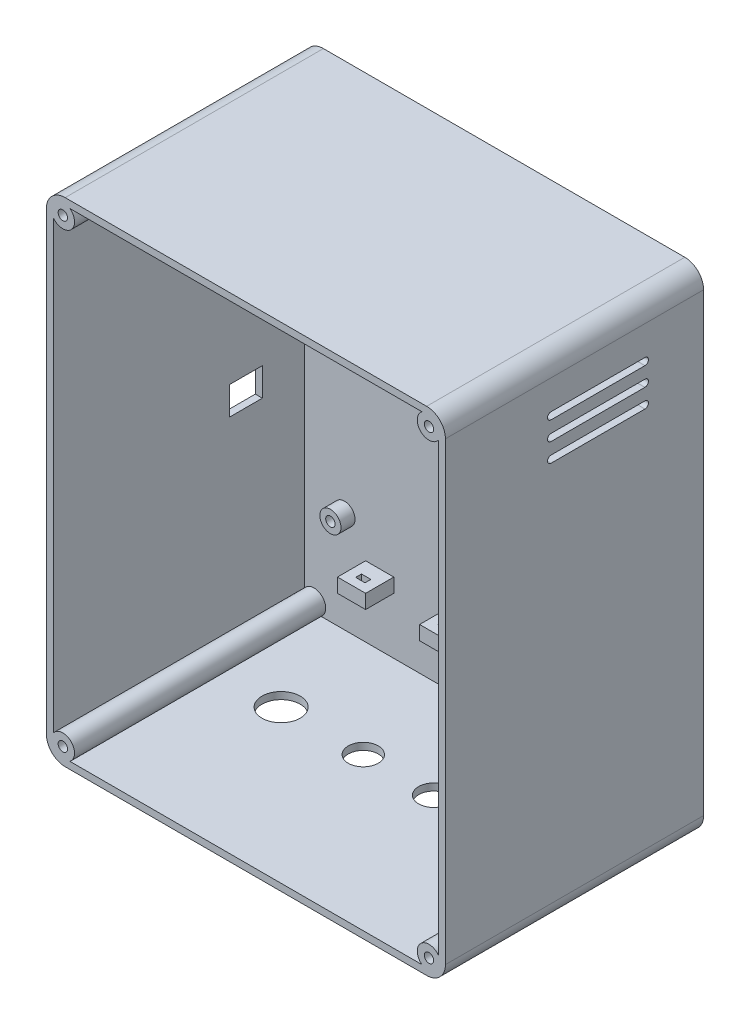
SolidWorks part; units mm, degrees
ref_plane "Front Plane" through (0, 0, 0) normal (0, 0, 1) x (1, 0, 0)
ref_plane "Top Plane" through (0, 0, 0) normal (0, 1, 0) x (1, 0, 0)
ref_plane "Right Plane" through (0, 0, 0) normal (1, 0, 0) x (0, 0, -1)
sketch "Sketch1" plane through (0, 0, 0) normal (0, 0, 1) x (1, 0, 0)
  line L0 (-77, 0) -> (77, 0)
  line L1 (85, 8) -> (85, 202)
  line L2 (77, 210) -> (-77, 210)
  line L3 (-85, 202) -> (-85, 8)
  arc A0 (-85, 8) -> (-77, 0) centre (-77, 8) ccw
  arc A1 (77, 0) -> (85, 8) centre (77, 8) ccw
  arc A2 (85, 202) -> (77, 210) centre (77, 202) ccw
  arc A3 (-77, 210) -> (-85, 202) centre (-77, 202) ccw
extrude "Block" add sketch "Sketch1" along normal blind 110
shell "Shell1" thickness 3
sketch "Sketch2" plane through (0, 0, 0) normal (0, 0, 1) x (1, 0, 0)
  circle A0 centre (-78, 7) radius 5
  circle A1 centre (78, 7) radius 5
  circle A2 centre (-78, 203) radius 5
  circle A3 centre (78, 203) radius 5
extrude "Corner columns" add sketch "Sketch2" along normal blind 110
ref_plane "P1_Front_110" through (0, 0, 110) normal (0, 0, 1) x (1, 0, 0)
sketch "Sketch3" plane through (0, 0, 110) normal (0, 0, 1) x (1, 0, 0)
  circle A0 centre (-78, 7) radius 2
  circle A1 centre (78, 7) radius 2
  circle A2 centre (-78, 203) radius 2
  circle A3 centre (78, 203) radius 2
extrude "Front panel insert holes" cut sketch "Sketch3" against normal blind 7
ref_plane "P2_Front_3" through (0, 0, 3) normal (0, 0, 1) x (1, 0, 0)
sketch "Sketch4" plane through (0, 0, 3) normal (0, 0, 1) x (1, 0, 0)
  circle A0 centre (-65, 46) radius 4.5
  circle A1 centre (65, 46) radius 4.5
  circle A2 centre (-65, 190) radius 4.5
  circle A3 centre (65, 190) radius 4.5
extrude "Plate bosses" add sketch "Sketch4" along normal blind 6
ref_plane "P3_Front_9" through (0, 0, 9) normal (0, 0, 1) x (1, 0, 0)
sketch "Sketch5" plane through (0, 0, 9) normal (0, 0, 1) x (1, 0, 0)
  circle A0 centre (-65, 46) radius 2
  circle A1 centre (65, 46) radius 2
  circle A2 centre (-65, 190) radius 2
  circle A3 centre (65, 190) radius 2
extrude "Plate insert holes" cut sketch "Sketch5" against normal blind 7
sketch "Sketch6" plane through (0, 0, 0) normal (0, 1, 0) x (1, 0, 0)
  circle A0 centre (-50, -45) radius 8.15
  circle A1 centre (-15, -45) radius 6.4
  circle A2 centre (15, -45) radius 6.4
  circle A3 centre (50, -45) radius 6.4
extrude "Cable gland holes" cut sketch "Sketch6" along normal blind 4
sketch "Sketch7" plane through (0, 0, 3) normal (0, 0, 1) x (1, 0, 0)
  line L1 (-56, 27) -> (-44, 27)
  line L2 (-56, 27) -> (-56, 33)
  line L3 (-56, 33) -> (-44, 33)
  line L4 (-44, 27) -> (-44, 33)
  line L5 (-56, 27) -> (-44, 33) construction
  line L6 (-56, 33) -> (-44, 27) construction
  line L7 (-21, 27) -> (-9, 27)
  line L8 (-21, 27) -> (-21, 33)
  line L9 (-21, 33) -> (-9, 33)
  line L10 (-9, 27) -> (-9, 33)
  line L11 (-21, 27) -> (-9, 33) construction
  line L12 (-21, 33) -> (-9, 27) construction
  line L13 (9, 27) -> (21, 27)
  line L14 (9, 27) -> (9, 33)
  line L15 (9, 33) -> (21, 33)
  line L16 (21, 27) -> (21, 33)
  line L17 (9, 27) -> (21, 33) construction
  line L18 (9, 33) -> (21, 27) construction
  line L19 (44, 27) -> (56, 27)
  line L20 (44, 27) -> (44, 33)
  line L21 (44, 33) -> (56, 33)
  line L22 (56, 27) -> (56, 33)
  line L23 (44, 27) -> (56, 33) construction
  line L24 (44, 33) -> (56, 27) construction
  point P0 (-50, 30)
  point P5 (-15, 30)
  point P10 (15, 30)
  point P15 (50, 30)
extrude "Cable tie bars" add sketch "Sketch7" along normal blind 12
ref_plane "P4_Top_26.99" through (0, 26.99, 0) normal (0, 1, 0) x (1, 0, 0)
sketch "Sketch8" plane through (0, 26.99, 0) normal (0, 1, 0) x (1, 0, 0)
  line L1 (-52, -11.25) -> (-48, -11.25)
  line L2 (-52, -11.25) -> (-52, -8.75)
  line L3 (-52, -8.75) -> (-48, -8.75)
  line L4 (-48, -11.25) -> (-48, -8.75)
  line L5 (-52, -11.25) -> (-48, -8.75) construction
  line L6 (-52, -8.75) -> (-48, -11.25) construction
  line L7 (-17, -11.25) -> (-13, -11.25)
  line L8 (-17, -11.25) -> (-17, -8.75)
  line L9 (-17, -8.75) -> (-13, -8.75)
  line L10 (-13, -11.25) -> (-13, -8.75)
  line L11 (-17, -11.25) -> (-13, -8.75) construction
  line L12 (-17, -8.75) -> (-13, -11.25) construction
  line L13 (13, -11.25) -> (17, -11.25)
  line L14 (13, -11.25) -> (13, -8.75)
  line L15 (13, -8.75) -> (17, -8.75)
  line L16 (17, -11.25) -> (17, -8.75)
  line L17 (13, -11.25) -> (17, -8.75) construction
  line L18 (13, -8.75) -> (17, -11.25) construction
  line L19 (48, -11.25) -> (52, -11.25)
  line L20 (48, -11.25) -> (48, -8.75)
  line L21 (48, -8.75) -> (52, -8.75)
  line L22 (52, -11.25) -> (52, -8.75)
  line L23 (48, -11.25) -> (52, -8.75) construction
  line L24 (48, -8.75) -> (52, -11.25) construction
  point P0 (-50, -10)
  point P5 (-15, -10)
  point P10 (15, -10)
  point P15 (50, -10)
extrude "Cable tie slots" cut sketch "Sketch8" along normal blind 6.02
ref_plane "P5_Right_-85" through (-85, 0, 0) normal (1, 0, 0) x (0, 0, -1)
sketch "Sketch9" plane through (-85, 0, 0) normal (1, 0, 0) x (0, 0, -1)
  line L1 (-35, 89) -> (-21, 89)
  line L2 (-35, 89) -> (-35, 101)
  line L3 (-35, 101) -> (-21, 101)
  line L4 (-21, 89) -> (-21, 101)
  line L5 (-35, 89) -> (-21, 101) construction
  line L6 (-35, 101) -> (-21, 89) construction
  point P0 (-28, 95)
extrude "USB access" cut sketch "Sketch9" along normal blind 4
ref_plane "P6_Right_-85" through (-85, 0, 0) normal (1, 0, 0) x (0, 0, -1)
sketch "Sketch10" plane through (-85, 0, 0) normal (1, 0, 0) x (0, 0, -1)
  line L0 (-25, 172) -> (-65, 172) construction
  line L1 (-25, 170.5) -> (-65, 170.5)
  line L2 (-25, 173.5) -> (-65, 173.5)
  line L3 (-25, 180) -> (-65, 180) construction
  line L4 (-25, 178.5) -> (-65, 178.5)
  line L5 (-25, 181.5) -> (-65, 181.5)
  line L6 (-25, 188) -> (-65, 188) construction
  line L7 (-25, 186.5) -> (-65, 186.5)
  line L8 (-25, 189.5) -> (-65, 189.5)
  arc A0 (-25, 170.5) -> (-25, 173.5) centre (-25, 172) ccw
  arc A1 (-65, 173.5) -> (-65, 170.5) centre (-65, 172) ccw
  arc A2 (-25, 178.5) -> (-25, 181.5) centre (-25, 180) ccw
  arc A3 (-65, 181.5) -> (-65, 178.5) centre (-65, 180) ccw
  arc A4 (-25, 186.5) -> (-25, 189.5) centre (-25, 188) ccw
  arc A5 (-65, 189.5) -> (-65, 186.5) centre (-65, 188) ccw
  point P2 (-45, 172)
  point P7 (-45, 180)
  point P14 (-45, 188)
  point P21 (0, 0)
extrude "Vents left" cut sketch "Sketch10" along normal blind 4
ref_plane "P7_Right_85" through (85, 0, 0) normal (1, 0, 0) x (0, 0, -1)
sketch "Sketch11" plane through (85, 0, 0) normal (1, 0, 0) x (0, 0, -1)
  line L0 (-25, 172) -> (-65, 172) construction
  line L1 (-25, 170.5) -> (-65, 170.5)
  line L2 (-25, 173.5) -> (-65, 173.5)
  line L3 (-25, 180) -> (-65, 180) construction
  line L4 (-25, 178.5) -> (-65, 178.5)
  line L5 (-25, 181.5) -> (-65, 181.5)
  line L6 (-25, 188) -> (-65, 188) construction
  line L7 (-25, 186.5) -> (-65, 186.5)
  line L8 (-25, 189.5) -> (-65, 189.5)
  arc A0 (-25, 170.5) -> (-25, 173.5) centre (-25, 172) ccw
  arc A1 (-65, 173.5) -> (-65, 170.5) centre (-65, 172) ccw
  arc A2 (-25, 178.5) -> (-25, 181.5) centre (-25, 180) ccw
  arc A3 (-65, 181.5) -> (-65, 178.5) centre (-65, 180) ccw
  arc A4 (-25, 186.5) -> (-25, 189.5) centre (-25, 188) ccw
  arc A5 (-65, 189.5) -> (-65, 186.5) centre (-65, 188) ccw
  point P2 (-45, 172)
  point P7 (-45, 180)
  point P14 (-45, 188)
  point P21 (0, 0)
extrude "Vents right" cut sketch "Sketch11" against normal blind 4
sketch "Sketch12" plane through (0, 0, 0) normal (0, 0, 1) x (1, 0, 0)
  circle A0 centre (-45, 165) radius 4.75
  circle A1 centre (45, 165) radius 4.75
extrude "Keyhole heads" cut sketch "Sketch12" along normal blind 4
sketch "Sketch13" plane through (0, 0, 0) normal (0, 0, 1) x (1, 0, 0)
  line L0 (-45, 165) -> (-45, 176) construction
  line L1 (-47.15, 165) -> (-47.15, 176)
  line L2 (-42.85, 165) -> (-42.85, 176)
  line L3 (45, 165) -> (45, 176) construction
  line L4 (42.85, 165) -> (42.85, 176)
  line L5 (47.15, 165) -> (47.15, 176)
  arc A0 (-47.15, 165) -> (-42.85, 165) centre (-45, 165) ccw
  arc A1 (-42.85, 176) -> (-47.15, 176) centre (-45, 176) ccw
  arc A2 (42.85, 165) -> (47.15, 165) centre (45, 165) ccw
  arc A3 (47.15, 176) -> (42.85, 176) centre (45, 176) ccw
  point P2 (-45, 170.5)
  point P7 (45, 170.5)
  point P14 (0, 0)
extrude "Keyhole slots" cut sketch "Sketch13" along normal blind 4
